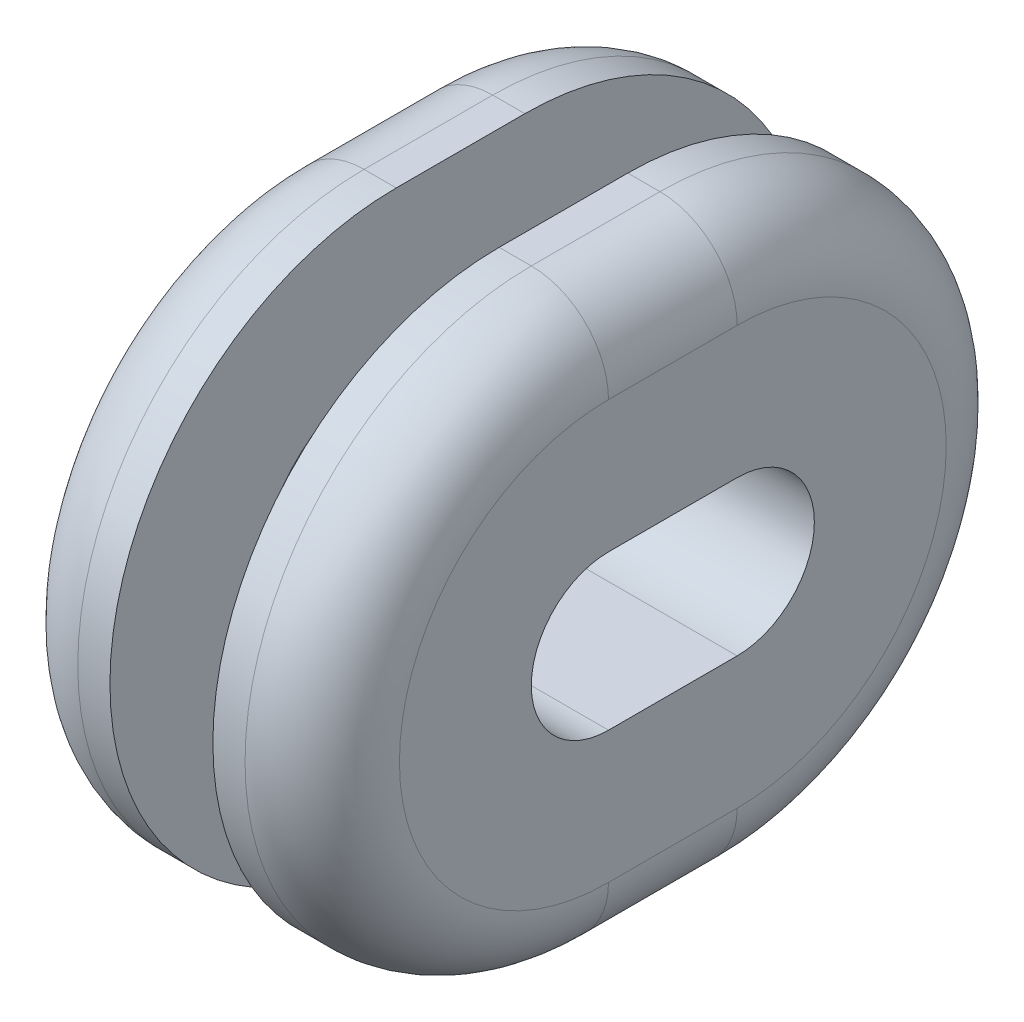
SolidWorks part; units mm, degrees
ref_plane "Спереди(Плоскость XY)" through (0, 0, 0) normal (0, 0, 1) x (1, 0, 0)
ref_plane "Сверху(Плоскость XZ)" through (0, 0, 0) normal (0, 1, 0) x (1, 0, 0)
ref_plane "Справа(Плоскость ZY)" through (0, 0, 0) normal (1, 0, 0) x (0, 0, -1)
sketch "Эскиз1" plane through (0, 0, 0) normal (0, 0, 1) x (1, 0, 0)
  line L0 (0, 0) -> (0, 1) construction
  line L1 (-0.8, 1) -> (0.8, 1)
  line L2 (-0.8, 1) -> (-0.8, 3.25)
  line L3 (-0.8, 3.25) -> (-2.5, 3.25)
  line L4 (-2.5, 3.25) -> (-2.5, 0)
  line L5 (-2.5, 0) -> (2.5, 0)
  line L6 (0.8, 1) -> (0.8, 3.25)
  line L7 (0.8, 3.25) -> (2.5, 3.25)
  line L8 (2.5, 3.25) -> (2.5, 0)
  line L9 (0, 0) -> (0, -2) construction
  line L10 (0, -2) -> (-6.7744, -2) construction
  point P5 (0, 1)
  dimension "D1" = 2
  dimension "D2" = 5.25
  dimension "D3" = 1.6
  dimension "D4" = 3
  dimension "D5" = 5
sketch "Эскиз3" plane through (0, 0, 0) normal (1, 0, 0) x (0, 0, -1)
  line L1 (0, 0) -> (0, -2) construction
  line L2 (-1, -1.2) -> (1, -1.2) construction
  line L3 (-1, 0) -> (1, 0)
  line L4 (-1, -2.4) -> (1, -2.4)
  line L5 (0, 0) -> (1.5, 0) construction
  arc A0 (-1, 0) -> (-1, -2.4) centre (-1, -1.2) ccw
  arc A1 (1, -2.4) -> (1, 0) centre (1, -1.2) ccw
  circle A2 centre (1, -1.2) radius 1.2 construction
  circle A4 centre (0, -2) radius 2 construction
  point P7 (0, -1.2)
  dimension "D3" = 2
  dimension "D2" = 2.4
sweep "По траектории2" add profiles "Эскиз1" path "Эскиз3"
fillet "Скругление1" radius 1.2 8 edges at (2.5, -1.2, 5.45) (-2.5, -1.2, 5.45) (2.5, -5.65, 0) (-2.5, -5.65, 0) (2.5, -1.2, -5.45) (-2.5, -1.2, -5.45)
